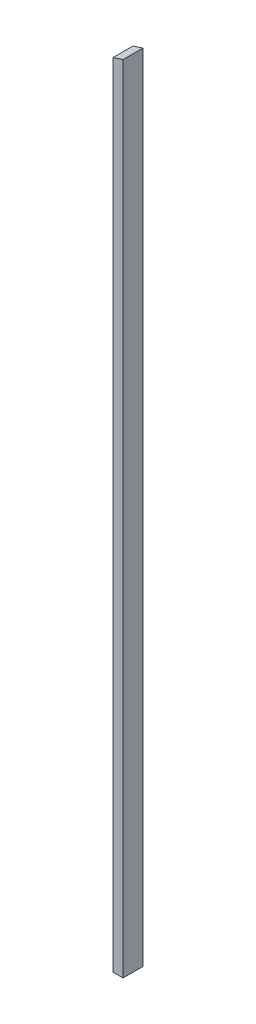
SolidWorks part; units mm, degrees
ref_plane "Спереди" through (0, 0, 0) normal (0, 0, 1) x (1, 0, 0)
ref_plane "Сверху" through (0, 0, 0) normal (0, 1, 0) x (1, 0, 0)
ref_plane "Справа" through (0, 0, 0) normal (1, 0, 0) x (0, 0, -1)
other "Configuration Table"
sketch "Эскиз1" plane through (0, 0, 0) normal (0, 1, 0) x (1, 0, 0)
  line L1 (12.5, 25) -> (-12.5, 25)
  line L2 (12.5, 25) -> (12.5, -25)
  line L3 (12.5, -25) -> (-12.5, -25)
  line L4 (-12.5, 25) -> (-12.5, -25)
  line L5 (12.5, 25) -> (-12.5, -25) construction
  line L6 (12.5, -25) -> (-12.5, 25) construction
  point P0 (0, 0)
extrude "Бобышка-Вытянуть1" add sketch "Эскиз1" along normal blind 2000
sketch "Эскиз2" plane through (0, 0, 25) normal (0, 0, 1) x (1, 0, 0)
  line L0 (-12.5, 2000) -> (-12.5, 1992.06)
  line L1 (-12.5, 2000) -> (-12.5, 0) construction
  line L2 (-12.5, 1992.06) -> (12.5, 2000)
  line L3 (12.5, 2000) -> (-12.5, 2000)
extrude "Вырез-Вытянуть1" cut sketch "Эскиз2" against normal blind 50
